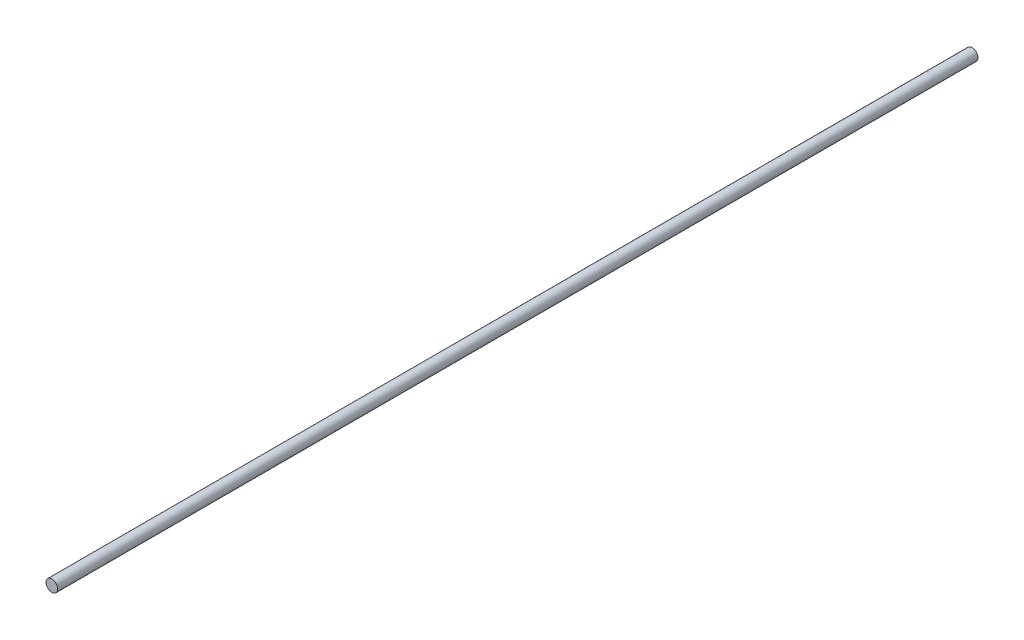
SolidWorks part; units mm, degrees
ref_plane "Ön Düzlem" through (0, 0, 0) normal (0, 0, 1) x (1, 0, 0)
ref_plane "Üst Düzlem" through (0, 0, 0) normal (0, 1, 0) x (1, 0, 0)
ref_plane "Sağ Düzlem" through (0, 0, 0) normal (1, 0, 0) x (0, 0, -1)
sketch "Çizim1" plane through (0, 0, 0) normal (0, 0, 1) x (1, 0, 0)
  circle A0 centre (0, 0) radius 4
  dimension "8" = 8
extrude "Yükseklik-Ekstrüzyon1" add sketch "Çizim1" along normal blind 630
